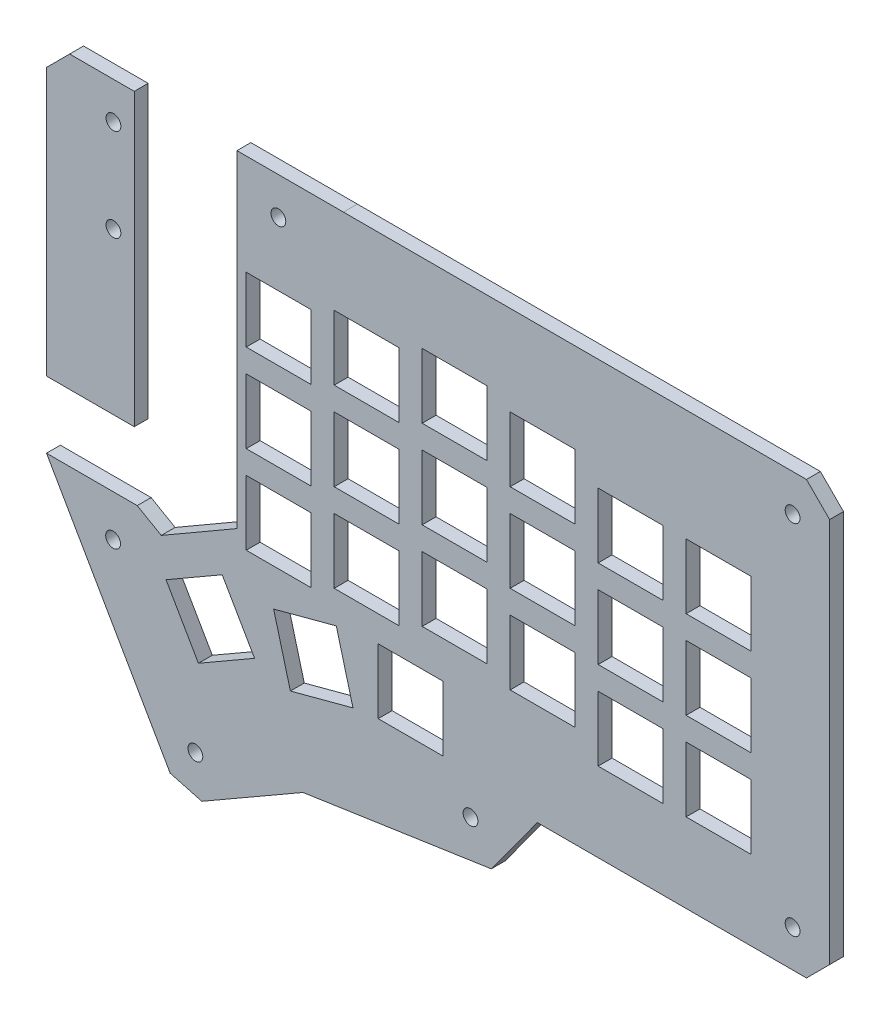
SolidWorks part; units mm, degrees
ref_plane "Plan de face" through (0, 0, 0) normal (0, 0, 1) x (1, 0, 0)
ref_plane "Plan de dessus" through (0, 0, 0) normal (0, 1, 0) x (1, 0, 0)
ref_plane "Plan de droite" through (0, 0, 0) normal (1, 0, 0) x (0, 0, -1)
sketch "Switchplate" plane through (0, 0, 0) normal (0, 0, 1) x (1, 0, 0)
  line L0 (-117.3419, -15.4198) -> (-103.3409, -15.4198)
  line L1 (-103.3409, -15.4198) -> (-103.3409, -29.4208)
  line L2 (-103.3409, -29.4208) -> (-117.3419, -29.4208)
  line L3 (-117.3419, -29.4208) -> (-117.3419, -15.4198)
  line L4 (-98.3406, -27.0457) -> (-98.3406, -13.0447)
  line L5 (-98.3406, -13.0447) -> (-84.3396, -13.0447)
  line L6 (-84.3396, -13.0447) -> (-84.3396, -27.0457)
  line L7 (-84.3396, -27.0457) -> (-98.3406, -27.0457)
  line L8 (-79.3392, -24.6705) -> (-79.3392, -10.6695)
  line L9 (-79.3392, -10.6695) -> (-65.3382, -10.6695)
  line L10 (-65.3382, -10.6695) -> (-65.3382, -24.6705)
  line L11 (-65.3382, -24.6705) -> (-79.3392, -24.6705)
  line L12 (-60.3379, -27.0457) -> (-60.3379, -13.0447)
  line L13 (-60.3379, -13.0447) -> (-46.3369, -13.0447)
  line L14 (-46.3369, -13.0447) -> (-46.3369, -27.0457)
  line L15 (-46.3369, -27.0457) -> (-60.3379, -27.0457)
  line L16 (-41.3365, -31.796) -> (-41.3365, -17.795)
  line L17 (-41.3365, -17.795) -> (-27.3355, -17.795)
  line L18 (-27.3355, -17.795) -> (-27.3355, -31.796)
  line L19 (-27.3355, -31.796) -> (-41.3365, -31.796)
  line L20 (-22.3347, -31.796) -> (-22.3347, -17.795)
  line L21 (-22.3347, -17.795) -> (-8.3337, -17.795)
  line L22 (-8.3337, -17.795) -> (-8.3337, -31.796)
  line L23 (-8.3337, -31.796) -> (-22.3347, -31.796)
  line L24 (-117.3419, -34.4212) -> (-103.3409, -34.4212)
  line L25 (-103.3409, -34.4212) -> (-103.3409, -48.4222)
  line L26 (-103.3409, -48.4222) -> (-117.3419, -48.4222)
  line L27 (-117.3419, -48.4222) -> (-117.3419, -34.4212)
  line L28 (-98.3406, -32.046) -> (-84.3396, -32.046)
  line L29 (-84.3396, -32.046) -> (-84.3396, -46.047)
  line L30 (-84.3396, -46.047) -> (-98.3406, -46.047)
  line L31 (-98.3406, -46.047) -> (-98.3406, -32.046)
  line L32 (-79.3392, -29.6709) -> (-65.3382, -29.6709)
  line L33 (-65.3382, -29.6709) -> (-65.3382, -43.6718)
  line L34 (-65.3382, -43.6718) -> (-79.3392, -43.6718)
  line L35 (-79.3392, -43.6718) -> (-79.3392, -29.6709)
  line L36 (-60.3379, -32.046) -> (-46.3369, -32.046)
  line L37 (-46.3369, -32.046) -> (-46.3369, -46.047)
  line L38 (-46.3369, -46.047) -> (-60.3379, -46.047)
  line L39 (-60.3379, -46.047) -> (-60.3379, -32.046)
  line L40 (-41.3365, -36.7964) -> (-27.3355, -36.7964)
  line L41 (-27.3355, -36.7964) -> (-27.3355, -50.7973)
  line L42 (-27.3355, -50.7973) -> (-41.3365, -50.7973)
  line L43 (-41.3365, -50.7973) -> (-41.3365, -36.7964)
  line L44 (-22.3347, -36.7964) -> (-8.3337, -36.7964)
  line L45 (-8.3337, -36.7964) -> (-8.3337, -50.7973)
  line L46 (-8.3337, -50.7973) -> (-22.3347, -50.7973)
  line L47 (-22.3347, -50.7973) -> (-22.3347, -36.7964)
  line L48 (-22.3347, -55.7977) -> (-8.3337, -55.7977)
  line L49 (-8.3337, -55.7977) -> (-8.3337, -69.7987)
  line L50 (-8.3337, -69.7987) -> (-22.3347, -69.7987)
  line L51 (-22.3347, -69.7987) -> (-22.3347, -55.7977)
  line L52 (-41.3365, -55.7977) -> (-27.3355, -55.7977)
  line L53 (-27.3355, -55.7977) -> (-27.3355, -69.7987)
  line L54 (-27.3355, -69.7987) -> (-41.3365, -69.7987)
  line L55 (-41.3365, -69.7987) -> (-41.3365, -55.7977)
  line L56 (-60.3379, -51.0474) -> (-46.3369, -51.0474)
  line L57 (-46.3369, -51.0474) -> (-46.3369, -65.0484)
  line L58 (-46.3369, -65.0484) -> (-60.3379, -65.0484)
  line L59 (-60.3379, -65.0484) -> (-60.3379, -51.0474)
  line L60 (-79.3392, -48.6722) -> (-65.3382, -48.6722)
  line L61 (-65.3382, -48.6722) -> (-65.3382, -62.6732)
  line L62 (-65.3382, -62.6732) -> (-79.3392, -62.6732)
  line L63 (-79.3392, -62.6732) -> (-79.3392, -48.6722)
  line L64 (-98.3406, -51.0474) -> (-84.3396, -51.0474)
  line L65 (-84.3396, -51.0474) -> (-84.3396, -65.0484)
  line L66 (-84.3396, -65.0484) -> (-98.3406, -65.0484)
  line L67 (-98.3406, -65.0484) -> (-98.3406, -51.0474)
  line L68 (-117.3419, -53.4225) -> (-103.3409, -53.4225)
  line L69 (-103.3409, -53.4225) -> (-103.3409, -67.4235)
  line L70 (-103.3409, -67.4235) -> (-117.3419, -67.4235)
  line L71 (-117.3419, -67.4235) -> (-117.3419, -53.4225)
  line L72 (-88.8399, -70.6738) -> (-74.8389, -70.6738)
  line L73 (-74.8389, -70.6738) -> (-74.8389, -84.6747)
  line L74 (-74.8389, -84.6747) -> (-88.8399, -84.6747)
  line L75 (-88.8399, -84.6747) -> (-88.8399, -70.6738)
  line L76 (-111.4175, -75.4665) -> (-97.8899, -71.8565)
  line L77 (-97.8899, -71.8565) -> (-94.28, -85.3841)
  line L78 (-94.28, -85.3841) -> (-107.8075, -88.9941)
  line L79 (-107.8075, -88.9941) -> (-111.4175, -75.4665)
  line L80 (-134.6581, -81.5997) -> (-122.5281, -74.6075)
  line L81 (-122.5281, -74.6075) -> (-115.5359, -86.7375)
  line L82 (-115.5359, -86.7375) -> (-127.6659, -93.7297)
  line L83 (-127.6659, -93.7297) -> (-134.6581, -81.5997)
  line L86 (-6.3391, -71.9336) -> (-62.0853, -71.9336) construction
  line L89 (-72.824, -86.6446) -> (-62.0853, -71.9336) construction
  line L96 (-109.7697, -91.4639) -> (-73.0906, -86.6918) construction
  line L97 (-124.664, -99.8297) -> (-110.3971, -91.5881) construction
  line L98 (-139.9408, -76.5013) -> (-126.7151, -99.4281) construction
  line L99 (-119.8527, -15.5421) -> (-139.6028, -15.5421) construction
  line L100 (-100.8528, -13.2921) -> (-118.8527, -13.2921) construction
  line L101 (-63.8455, -8.5421) -> (-80.8528, -8.5421) construction
  line L102 (-44.8455, -10.792) -> (-62.8485, -10.792) construction
  line L103 (-25.8456, -15.5421) -> (-43.8486, -15.5421) construction
  line L104 (-6.8456, -15.5421) -> (-23.8529, -15.5421) construction
  line L105 (-6.2741, -71.3672) -> (-6.2741, -16.1136) construction
  line L106 (-23.8529, -71.9423) -> (-6.8456, -71.9423) construction
  line L107 (-61.8455, -71.9423) -> (-25.8456, -71.9423) construction
  line L108 (-72.6738, -86.4911) -> (-62.1363, -72.0583) construction
  line L109 (-140.1743, -16.1136) -> (-140.1743, -75.5958) construction
  line L110 (-134.3462, 1.5705) -> (-134.3466, -55.7217) construction
  line L111 (-134.3466, -55.7217) -> (-160.479, -70.8411) construction
  line L112 (-160.479, -70.8411) -> (-133.7613, -117.344)
  line L113 (-126.937, -119.1852) -> (-105.0783, -106.604)
  line L114 (-105.0783, -106.604) -> (-64.4097, -100.5586)
  line L115 (-64.4097, -100.5586) -> (-54.4636, -86.9336)
  line L116 (3.6609, -86.9336) -> (-54.4636, -86.9336)
  line L117 (8.6609, -81.9336) -> (8.6609, 1.315)
  line L122 (3.6609, 6.3153) -> (-96.3444, 6.3209)
  line L129 (8.6609, -86.9336) -> (8.6609, -0.6796) construction
  line L130 (-48.3431, 6.3182) -> (-96.3444, 6.3209) construction
  line L131 (-115.3458, 1.5705) -> (-134.3462, 1.5705) construction
  line L132 (-160.479, -3.4295) -> (-160.479, -70.8411)
  line L134 (-119.3463, 1.5705) -> (-119.3466, -64.3728)
  line L135 (-119.3466, -64.3728) -> (-135.695, -73.8315)
  line L136 (-140.0228, -71.3355) -> (-140.0228, 1.5705) construction
  line L138 (-160.479, -70.8411) -> (-131.2704, -121.6794) construction
  line L139 (-131.2704, -121.6794) -> (-105.0783, -106.604) construction
  line L140 (-133.7613, -117.344) -> (-126.937, -119.1852)
  line L142 (8.6609, 1.315) -> (3.6609, 6.3153)
  line L143 (8.6609, -86.9336) -> (-54.4636, -86.9336) construction
  line L147 (-103.3409, 6.3209) -> (-96.3444, 6.3209)
  line L148 (-103.3409, 6.3209) -> (-119.3463, 6.3209)
  line L149 (-119.3463, 6.3209) -> (-119.3463, 1.5705)
  line L150 (-140.0228, 1.5705) -> (-140.0228, 6.3209) construction
  line L151 (-141.5228, 6.3209) -> (-155.479, 6.3209)
  line L152 (-160.479, 1.3209) -> (-160.479, -3.4295)
  line L153 (-155.479, 6.3209) -> (-160.479, 1.3209)
  line L154 (8.6609, -1.685) -> (-119.3463, -1.6779) construction
  line L155 (-146.0924, -79.8227) -> (-128.3223, -110.752) construction
  line L156 (-128.3223, -110.752) -> (-107.7547, -98.9139) construction
  line L157 (-140.8899, -76.8336) -> (-126.1111, -102.5565) construction
  line L158 (-126.1111, -102.5565) -> (-109.762, -93.1464) construction
  line L159 (-109.762, -93.1464) -> (-72.2631, -87.5722) construction
  line L160 (-72.2631, -87.5722) -> (-61.5772, -72.9336) construction
  line L161 (-5.3391, -72.9336) -> (-61.5772, -72.9336) construction
  line L162 (-5.3391, -72.9336) -> (-5.3391, -14.6796) construction
  line L163 (-5.3391, -14.6796) -> (-43.3418, -14.6796) construction
  line L164 (-43.3418, -14.6796) -> (-43.3418, -9.9293) construction
  line L165 (-43.3418, -9.9293) -> (-62.3431, -9.9293) construction
  line L166 (-62.3431, -9.9293) -> (-62.3431, -7.681) construction
  line L167 (-62.3431, -7.681) -> (-82.3444, -7.6799) construction
  line L168 (-82.3444, -7.6799) -> (-82.3444, -9.9293) construction
  line L169 (-82.3444, -9.9293) -> (-101.3458, -9.9293) construction
  line L170 (-101.3458, -9.9293) -> (-101.3458, -12.4295) construction
  line L171 (-101.3458, -12.4295) -> (-120.3463, -12.4295) construction
  line L172 (-120.3463, -12.4295) -> (-120.3466, -64.3728) construction
  line L173 (-119.8474, -63.5072) -> (-140.5236, -75.4699) construction
  line L174 (-107.7547, -98.9139) -> (-68.8973, -93.1378) construction
  line L175 (-68.8973, -93.1378) -> (-58.5285, -78.9336) construction
  line L176 (0.6609, -78.9336) -> (-58.5285, -78.9336) construction
  line L177 (0.6609, -78.9336) -> (0.6609, -1.6845) construction
  line L178 (-62.3428, -1.681) -> (-82.3441, -1.6799) construction
  line L179 (0.6609, -78.9336) -> (0.6609, -14.6796) construction
  line L180 (-146.0228, -76.3355) -> (-146.0228, 1.5705) construction
  line L181 (-140.0228, -76.3355) -> (-140.0228, 1.5705) construction
  line L182 (-135.695, -73.8315) -> (-141.5228, -70.4704)
  line L185 (8.6609, -81.9336) -> (3.6609, -86.9336)
  line L186 (-146.0228, -1.6779) -> (-146.0228, -19.3841) construction
  line L187 (-146.0228, -1.6779) -> (-146.0228, -21.6824) construction
  line L188 (-141.5228, -70.4704) -> (-141.5228, 1.5705)
  line L189 (-141.5228, 1.5705) -> (-141.5228, 6.3209)
  line L191 (-141.5228, -71.3355) -> (-141.5228, 1.5705) construction
  line L217 (-6.3391, -71.9336) -> (-6.3391, -15.6796) construction
  line L220 (-6.3391, -15.6796) -> (-44.3418, -15.6796) construction
  line L221 (-44.3418, -15.6796) -> (-44.3418, -10.9293) construction
  line L222 (-44.3418, -10.9293) -> (-63.3431, -10.9293) construction
  line L223 (-63.3431, -10.9293) -> (-63.3431, -8.681) construction
  line L224 (-63.3431, -8.681) -> (-81.3444, -8.68) construction
  line L225 (-81.3444, -8.68) -> (-81.3444, -10.9293) construction
  line L226 (-81.3444, -10.9293) -> (-100.3458, -10.9293) construction
  line L227 (-100.3458, -10.9293) -> (-100.3458, -13.4295) construction
  line L228 (-100.3458, -13.4295) -> (-119.3463, -13.4295) construction
  line L231 (-119.3463, -13.4295) -> (-119.3466, -64.3728) construction
  line L232 (-119.3466, -64.3728) -> (-140.0228, -76.3355) construction
  line L233 (-140.0228, -76.3355) -> (-125.7426, -101.1906) construction
  line L234 (-125.7426, -101.1906) -> (-110.0965, -92.1851) construction
  line L235 (-110.0965, -92.1851) -> (-72.824, -86.6446) construction
  line L328 (-48.3431, 4.0707) -> (-48.3431, 6.3182) construction
  line L329 (-29.3418, 4.0707) -> (-48.3431, 4.0707) construction
  line L330 (-29.3418, -0.6796) -> (-29.3418, 4.0707) construction
  line L331 (8.6609, -0.6796) -> (-29.3418, -0.6796) construction
  line L332 (-115.3458, 4.0707) -> (-115.3458, 1.5705) construction
  line L333 (-96.3444, 4.0707) -> (-115.3458, 4.0707) construction
  line L334 (-96.3444, 6.3209) -> (-96.3444, 4.0707) construction
  circle A2 centre (0.6609, -1.6845) radius 1.6
  circle A3 centre (0.6609, -1.6845) radius 3 construction
  circle A4 centre (-110.3971, -1.6784) radius 1.6
  circle A5 centre (0.6609, -78.9336) radius 1.6
  circle A6 centre (-68.8973, -93.1378) radius 1.6
  circle A7 centre (-128.3223, -110.752) radius 1.6
  circle A8 centre (-146.0924, -79.8227) radius 1.6
  circle A9 centre (-146.0228, -1.6779) radius 1.6
  circle A10 centre (-146.0228, -21.6824) radius 1.6
  point P138 (-160.479, 1.5705)
  point P139 (8.6609, 6.315)
  point P150 (-160.479, 6.3209)
  point P200 (8.6609, -86.9336)
  dimension "D3" = 3.2
  dimension "D4" = 6
  dimension "D6" = 3.2
  dimension "D7" = 3.2
  dimension "D8" = 3.2
  dimension "D9" = 3.2
  dimension "D10" = 3.2
  dimension "D15" = 3.2
  dimension "D16" = 3.2
  dimension "D2" = 6
  dimension "D1" = 15
  dimension "D5" = 1
  dimension "D13" = 6
  dimension "D17" = 1.5
extrude "Boss.-Extru.2" add sketch "Switchplate" along normal blind 3
sketch "Esquisse1" plane through (0, 0, 3) normal (0, 0, 1) x (1, 0, 0)
  line L0 (-160.479, -70.8411) -> (-140.0228, -70.8411)
  line L1 (-140.0228, -71.3355) -> (-140.0228, 1.5705) construction
  line L2 (-117.3419, -53.4225) -> (-140.0228, -53.4225) construction
  line L3 (-140.0228, -53.4225) -> (-140.0228, -56.4207) construction
  line L4 (-140.0228, -56.4207) -> (-140.0228, -70.8411)
  line L5 (-140.0228, -56.4207) -> (-160.479, -56.4207)
  line L6 (-160.479, -3.4295) -> (-160.479, -70.8411) construction
  line L7 (-160.479, -56.4207) -> (-160.479, -70.8411)
extrude "Enlèv. mat.-Extru.1" cut sketch "Esquisse1" against normal blind 10
sketch "Esquisse2" plane through (0, 0, 3) normal (0, 0, 1) x (1, 0, 0)
  line L0 (-81.3444, -8.68) -> (-81.3444, -10.9293) construction
  line L1 (-63.3431, -8.681) -> (-81.3444, -8.68) construction
  line L2 (-63.3431, -10.9293) -> (-63.3431, -8.681) construction
  line L3 (-44.3418, -10.9293) -> (-63.3431, -10.9293) construction
  line L4 (-44.3418, -15.6796) -> (-44.3418, -10.9293) construction
  line L5 (-6.3391, -15.6796) -> (-44.3418, -15.6796) construction
  line L6 (-6.3391, -71.9336) -> (-6.3391, -15.6796) construction
  line L7 (-6.3391, -71.9336) -> (-62.0853, -71.9336) construction
  line L8 (-72.824, -86.6446) -> (-62.0853, -71.9336) construction
  line L9 (-110.0965, -92.1851) -> (-72.824, -86.6446) construction
  line L10 (-125.7426, -101.1906) -> (-110.0965, -92.1851) construction
  line L11 (-140.0228, -76.3355) -> (-125.7426, -101.1906) construction
  line L12 (-119.3466, -64.3728) -> (-140.0228, -76.3355) construction
  line L13 (-119.3463, -13.4295) -> (-119.3466, -64.3728) construction
  line L14 (-100.3458, -13.4295) -> (-119.3463, -13.4295) construction
  line L15 (-100.3458, -10.9293) -> (-100.3458, -13.4295) construction
  line L16 (-81.3444, -10.9293) -> (-100.3458, -10.9293) construction
  line L17 (-81.3444, -8.68) -> (-81.3444, -10.9293)
  line L18 (-63.3431, -8.681) -> (-81.3444, -8.68)
  line L19 (-63.3431, -10.9293) -> (-63.3431, -8.681)
  line L20 (-44.3418, -10.9293) -> (-63.3431, -10.9293)
  line L21 (-44.3418, -15.6796) -> (-44.3418, -10.9293)
  line L22 (-6.3391, -15.6796) -> (-44.3418, -15.6796)
  line L23 (-6.3391, -71.9336) -> (-6.3391, -15.6796)
  line L24 (-6.3391, -71.9336) -> (-62.0853, -71.9336)
  line L25 (-72.824, -86.6446) -> (-62.0853, -71.9336)
  line L26 (-110.0965, -92.1851) -> (-72.824, -86.6446)
  line L27 (-125.7426, -101.1906) -> (-110.0965, -92.1851)
  line L28 (-140.0228, -76.3355) -> (-125.7426, -101.1906)
  line L29 (-119.3466, -64.3728) -> (-140.0228, -76.3355)
  line L30 (-119.3463, -13.4295) -> (-119.3466, -64.3728)
  line L31 (-100.3458, -13.4295) -> (-119.3463, -13.4295)
  line L32 (-100.3458, -10.9293) -> (-100.3458, -13.4295)
  line L33 (-81.3444, -10.9293) -> (-100.3458, -10.9293)
  line L34 (-127.6659, -93.7297) -> (-134.6581, -81.5997) construction
  line L35 (-115.5359, -86.7375) -> (-127.6659, -93.7297) construction
  line L36 (-122.5281, -74.6075) -> (-115.5359, -86.7375) construction
  line L37 (-134.6581, -81.5997) -> (-122.5281, -74.6075) construction
  line L38 (-107.8075, -88.9941) -> (-111.4175, -75.4665) construction
  line L39 (-94.28, -85.3841) -> (-107.8075, -88.9941) construction
  line L40 (-97.8899, -71.8565) -> (-94.28, -85.3841) construction
  line L41 (-111.4175, -75.4665) -> (-97.8899, -71.8565) construction
  line L42 (-88.8399, -84.6747) -> (-88.8399, -70.6738) construction
  line L43 (-74.8389, -84.6747) -> (-88.8399, -84.6747) construction
  line L44 (-74.8389, -70.6738) -> (-74.8389, -84.6747) construction
  line L45 (-88.8399, -70.6738) -> (-74.8389, -70.6738) construction
  line L46 (-98.3406, -65.0484) -> (-98.3406, -51.0474) construction
  line L47 (-84.3396, -65.0484) -> (-98.3406, -65.0484) construction
  line L48 (-84.3396, -51.0474) -> (-84.3396, -65.0484) construction
  line L49 (-98.3406, -51.0474) -> (-84.3396, -51.0474) construction
  line L50 (-117.3419, -67.4235) -> (-117.3419, -53.4225) construction
  line L51 (-103.3409, -67.4235) -> (-117.3419, -67.4235) construction
  line L52 (-103.3409, -53.4225) -> (-103.3409, -67.4235) construction
  line L53 (-117.3419, -53.4225) -> (-103.3409, -53.4225) construction
  line L54 (-117.3419, -48.4222) -> (-117.3419, -34.4212) construction
  line L55 (-103.3409, -48.4222) -> (-117.3419, -48.4222) construction
  line L56 (-103.3409, -34.4212) -> (-103.3409, -48.4222) construction
  line L57 (-117.3419, -34.4212) -> (-103.3409, -34.4212) construction
  line L58 (-98.3406, -46.047) -> (-98.3406, -32.046) construction
  line L59 (-84.3396, -46.047) -> (-98.3406, -46.047) construction
  line L60 (-84.3396, -32.046) -> (-84.3396, -46.047) construction
  line L61 (-98.3406, -32.046) -> (-84.3396, -32.046) construction
  line L62 (-79.3392, -43.6718) -> (-79.3392, -29.6709) construction
  line L63 (-65.3382, -43.6718) -> (-79.3392, -43.6718) construction
  line L64 (-65.3382, -29.6709) -> (-65.3382, -43.6718) construction
  line L65 (-79.3392, -29.6709) -> (-65.3382, -29.6709) construction
  line L66 (-60.3379, -46.047) -> (-60.3379, -32.046) construction
  line L67 (-46.3369, -46.047) -> (-60.3379, -46.047) construction
  line L68 (-46.3369, -32.046) -> (-46.3369, -46.047) construction
  line L69 (-60.3379, -32.046) -> (-46.3369, -32.046) construction
  line L70 (-79.3392, -62.6732) -> (-79.3392, -48.6722) construction
  line L71 (-65.3382, -62.6732) -> (-79.3392, -62.6732) construction
  line L72 (-65.3382, -48.6722) -> (-65.3382, -62.6732) construction
  line L73 (-79.3392, -48.6722) -> (-65.3382, -48.6722) construction
  line L74 (-60.3379, -65.0484) -> (-60.3379, -51.0474) construction
  line L75 (-46.3369, -65.0484) -> (-60.3379, -65.0484) construction
  line L76 (-46.3369, -51.0474) -> (-46.3369, -65.0484) construction
  line L77 (-60.3379, -51.0474) -> (-46.3369, -51.0474) construction
  line L78 (-41.3365, -69.7987) -> (-41.3365, -55.7977) construction
  line L79 (-27.3355, -69.7987) -> (-41.3365, -69.7987) construction
  line L80 (-27.3355, -55.7977) -> (-27.3355, -69.7987) construction
  line L81 (-41.3365, -55.7977) -> (-27.3355, -55.7977) construction
  line L82 (-22.3347, -69.7987) -> (-22.3347, -55.7977) construction
  line L83 (-8.3337, -69.7987) -> (-22.3347, -69.7987) construction
  line L84 (-8.3337, -55.7977) -> (-8.3337, -69.7987) construction
  line L85 (-22.3347, -55.7977) -> (-8.3337, -55.7977) construction
  line L86 (-41.3365, -50.7973) -> (-41.3365, -36.7964) construction
  line L87 (-27.3355, -50.7973) -> (-41.3365, -50.7973) construction
  line L88 (-27.3355, -36.7964) -> (-27.3355, -50.7973) construction
  line L89 (-41.3365, -36.7964) -> (-27.3355, -36.7964) construction
  line L90 (-22.3347, -50.7973) -> (-22.3347, -36.7964) construction
  line L91 (-8.3337, -50.7973) -> (-22.3347, -50.7973) construction
  line L92 (-8.3337, -36.7964) -> (-8.3337, -50.7973) construction
  line L93 (-22.3347, -36.7964) -> (-8.3337, -36.7964) construction
  line L94 (-22.3347, -31.796) -> (-22.3347, -17.795) construction
  line L95 (-8.3337, -31.796) -> (-22.3347, -31.796) construction
  line L96 (-8.3337, -17.795) -> (-8.3337, -31.796) construction
  line L97 (-22.3347, -17.795) -> (-8.3337, -17.795) construction
  line L98 (-41.3365, -31.796) -> (-41.3365, -17.795) construction
  line L99 (-27.3355, -31.796) -> (-41.3365, -31.796) construction
  line L100 (-27.3355, -17.795) -> (-27.3355, -31.796) construction
  line L101 (-41.3365, -17.795) -> (-27.3355, -17.795) construction
  line L102 (-60.3379, -27.0457) -> (-60.3379, -13.0447) construction
  line L103 (-46.3369, -27.0457) -> (-60.3379, -27.0457) construction
  line L104 (-46.3369, -13.0447) -> (-46.3369, -27.0457) construction
  line L105 (-60.3379, -13.0447) -> (-46.3369, -13.0447) construction
  line L106 (-79.3392, -24.6705) -> (-79.3392, -10.6695) construction
  line L107 (-65.3382, -24.6705) -> (-79.3392, -24.6705) construction
  line L108 (-65.3382, -10.6695) -> (-65.3382, -24.6705) construction
  line L109 (-79.3392, -10.6695) -> (-65.3382, -10.6695) construction
  line L110 (-98.3406, -27.0457) -> (-98.3406, -13.0447) construction
  line L111 (-84.3396, -27.0457) -> (-98.3406, -27.0457) construction
  line L112 (-84.3396, -13.0447) -> (-84.3396, -27.0457) construction
  line L113 (-98.3406, -13.0447) -> (-84.3396, -13.0447) construction
  line L114 (-117.3419, -29.4208) -> (-117.3419, -15.4198) construction
  line L115 (-103.3409, -29.4208) -> (-117.3419, -29.4208) construction
  line L116 (-103.3409, -15.4198) -> (-103.3409, -29.4208) construction
  line L117 (-117.3419, -15.4198) -> (-103.3409, -15.4198) construction
  line L118 (-127.6659, -93.7297) -> (-134.6581, -81.5997)
  line L119 (-115.5359, -86.7375) -> (-127.6659, -93.7297)
  line L120 (-122.5281, -74.6075) -> (-115.5359, -86.7375)
  line L121 (-134.6581, -81.5997) -> (-122.5281, -74.6075)
  line L122 (-107.8075, -88.9941) -> (-111.4175, -75.4665)
  line L123 (-94.28, -85.3841) -> (-107.8075, -88.9941)
  line L124 (-97.8899, -71.8565) -> (-94.28, -85.3841)
  line L125 (-111.4175, -75.4665) -> (-97.8899, -71.8565)
  line L126 (-88.8399, -84.6747) -> (-88.8399, -70.6738)
  line L127 (-74.8389, -84.6747) -> (-88.8399, -84.6747)
  line L128 (-74.8389, -70.6738) -> (-74.8389, -84.6747)
  line L129 (-88.8399, -70.6738) -> (-74.8389, -70.6738)
  line L130 (-98.3406, -65.0484) -> (-98.3406, -51.0474)
  line L131 (-84.3396, -65.0484) -> (-98.3406, -65.0484)
  line L132 (-84.3396, -51.0474) -> (-84.3396, -65.0484)
  line L133 (-98.3406, -51.0474) -> (-84.3396, -51.0474)
  line L134 (-117.3419, -67.4235) -> (-117.3419, -53.4225)
  line L135 (-103.3409, -67.4235) -> (-117.3419, -67.4235)
  line L136 (-103.3409, -53.4225) -> (-103.3409, -67.4235)
  line L137 (-117.3419, -53.4225) -> (-103.3409, -53.4225)
  line L138 (-117.3419, -48.4222) -> (-117.3419, -34.4212)
  line L139 (-103.3409, -48.4222) -> (-117.3419, -48.4222)
  line L140 (-103.3409, -34.4212) -> (-103.3409, -48.4222)
  line L141 (-117.3419, -34.4212) -> (-103.3409, -34.4212)
  line L142 (-98.3406, -46.047) -> (-98.3406, -32.046)
  line L143 (-84.3396, -46.047) -> (-98.3406, -46.047)
  line L144 (-84.3396, -32.046) -> (-84.3396, -46.047)
  line L145 (-98.3406, -32.046) -> (-84.3396, -32.046)
  line L146 (-79.3392, -43.6718) -> (-79.3392, -29.6709)
  line L147 (-65.3382, -43.6718) -> (-79.3392, -43.6718)
  line L148 (-65.3382, -29.6709) -> (-65.3382, -43.6718)
  line L149 (-79.3392, -29.6709) -> (-65.3382, -29.6709)
  line L150 (-60.3379, -46.047) -> (-60.3379, -32.046)
  line L151 (-46.3369, -46.047) -> (-60.3379, -46.047)
  line L152 (-46.3369, -32.046) -> (-46.3369, -46.047)
  line L153 (-60.3379, -32.046) -> (-46.3369, -32.046)
  line L154 (-79.3392, -62.6732) -> (-79.3392, -48.6722)
  line L155 (-65.3382, -62.6732) -> (-79.3392, -62.6732)
  line L156 (-65.3382, -48.6722) -> (-65.3382, -62.6732)
  line L157 (-79.3392, -48.6722) -> (-65.3382, -48.6722)
  line L158 (-60.3379, -65.0484) -> (-60.3379, -51.0474)
  line L159 (-46.3369, -65.0484) -> (-60.3379, -65.0484)
  line L160 (-46.3369, -51.0474) -> (-46.3369, -65.0484)
  line L161 (-60.3379, -51.0474) -> (-46.3369, -51.0474)
  line L162 (-41.3365, -69.7987) -> (-41.3365, -55.7977)
  line L163 (-27.3355, -69.7987) -> (-41.3365, -69.7987)
  line L164 (-27.3355, -55.7977) -> (-27.3355, -69.7987)
  line L165 (-41.3365, -55.7977) -> (-27.3355, -55.7977)
  line L166 (-22.3347, -69.7987) -> (-22.3347, -55.7977)
  line L167 (-8.3337, -69.7987) -> (-22.3347, -69.7987)
  line L168 (-8.3337, -55.7977) -> (-8.3337, -69.7987)
  line L169 (-22.3347, -55.7977) -> (-8.3337, -55.7977)
  line L170 (-41.3365, -50.7973) -> (-41.3365, -36.7964)
  line L171 (-27.3355, -50.7973) -> (-41.3365, -50.7973)
  line L172 (-27.3355, -36.7964) -> (-27.3355, -50.7973)
  line L173 (-41.3365, -36.7964) -> (-27.3355, -36.7964)
  line L174 (-22.3347, -50.7973) -> (-22.3347, -36.7964)
  line L175 (-8.3337, -50.7973) -> (-22.3347, -50.7973)
  line L176 (-8.3337, -36.7964) -> (-8.3337, -50.7973)
  line L177 (-22.3347, -36.7964) -> (-8.3337, -36.7964)
  line L178 (-22.3347, -31.796) -> (-22.3347, -17.795)
  line L179 (-8.3337, -31.796) -> (-22.3347, -31.796)
  line L180 (-8.3337, -17.795) -> (-8.3337, -31.796)
  line L181 (-22.3347, -17.795) -> (-8.3337, -17.795)
  line L182 (-41.3365, -31.796) -> (-41.3365, -17.795)
  line L183 (-27.3355, -31.796) -> (-41.3365, -31.796)
  line L184 (-27.3355, -17.795) -> (-27.3355, -31.796)
  line L185 (-41.3365, -17.795) -> (-27.3355, -17.795)
  line L186 (-60.3379, -27.0457) -> (-60.3379, -13.0447)
  line L187 (-46.3369, -27.0457) -> (-60.3379, -27.0457)
  line L188 (-46.3369, -13.0447) -> (-46.3369, -27.0457)
  line L189 (-60.3379, -13.0447) -> (-46.3369, -13.0447)
  line L190 (-79.3392, -24.6705) -> (-79.3392, -10.6695)
  line L191 (-65.3382, -24.6705) -> (-79.3392, -24.6705)
  line L192 (-65.3382, -10.6695) -> (-65.3382, -24.6705)
  line L193 (-79.3392, -10.6695) -> (-65.3382, -10.6695)
  line L194 (-98.3406, -27.0457) -> (-98.3406, -13.0447)
  line L195 (-84.3396, -27.0457) -> (-98.3406, -27.0457)
  line L196 (-84.3396, -13.0447) -> (-84.3396, -27.0457)
  line L197 (-98.3406, -13.0447) -> (-84.3396, -13.0447)
  line L198 (-117.3419, -29.4208) -> (-117.3419, -15.4198)
  line L199 (-103.3409, -29.4208) -> (-117.3419, -29.4208)
  line L200 (-103.3409, -15.4198) -> (-103.3409, -29.4208)
  line L201 (-117.3419, -15.4198) -> (-103.3409, -15.4198)
